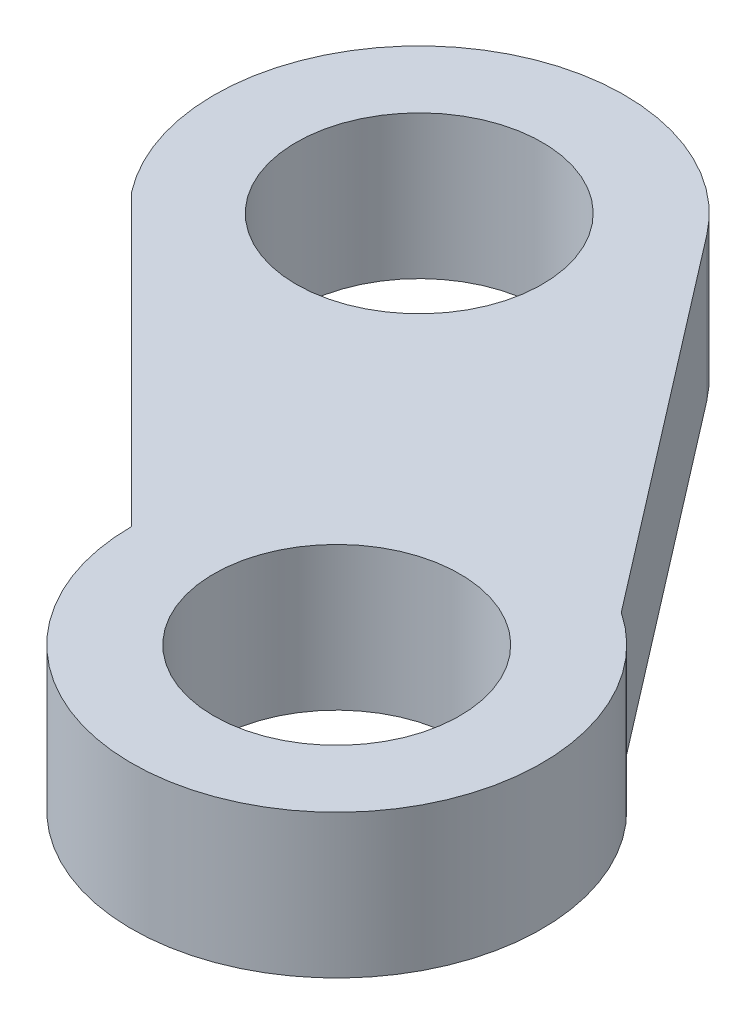
SolidWorks part; units mm, degrees
ref_plane "Front Plane" through (0, 0, 0) normal (0, 0, 1) x (1, 0, 0)
ref_plane "Top Plane" through (0, 0, 0) normal (0, 1, 0) x (1, 0, 0)
ref_plane "Right Plane" through (0, 0, 0) normal (1, 0, 0) x (0, 0, -1)
sketch "Sketch1" plane through (0, 0, 0) normal (0, 1, 0) x (1, 0, 0)
  line L0 (0, 0) -> (-65.1119, 0) construction
  line L1 (0, 0) -> (78.1941, 0) construction
  line L2 (-50, 0) -> (-120.7107, 70.7107)
  line L3 (27.8496, 41.5259) -> (-41.4258, 131.6526)
  line L4 (-120.7107, 70.7107) -> (-41.4258, 131.6526) construction
  circle A0 centre (0, 0) radius 30
  arc A1 (-50, 0) -> (27.8496, 41.5259) centre (0, 0) ccw
  circle A2 centre (-81.0683, 101.1816) radius 30
  arc A3 (-41.4258, 131.6526) -> (-111.5392, 61.5392) centre (-81.0683, 101.1816) ccw
  dimension "D1" = 20
  dimension "D4" = 60
  dimension "D5" = 20
  dimension "D6" = 60
  dimension "D2" = 135
  dimension "D3" = 100
extrude "Boss-Extrude1" add sketch "Sketch1" along normal blind 35 contours L3 A3 L2 A1 A0 A2
